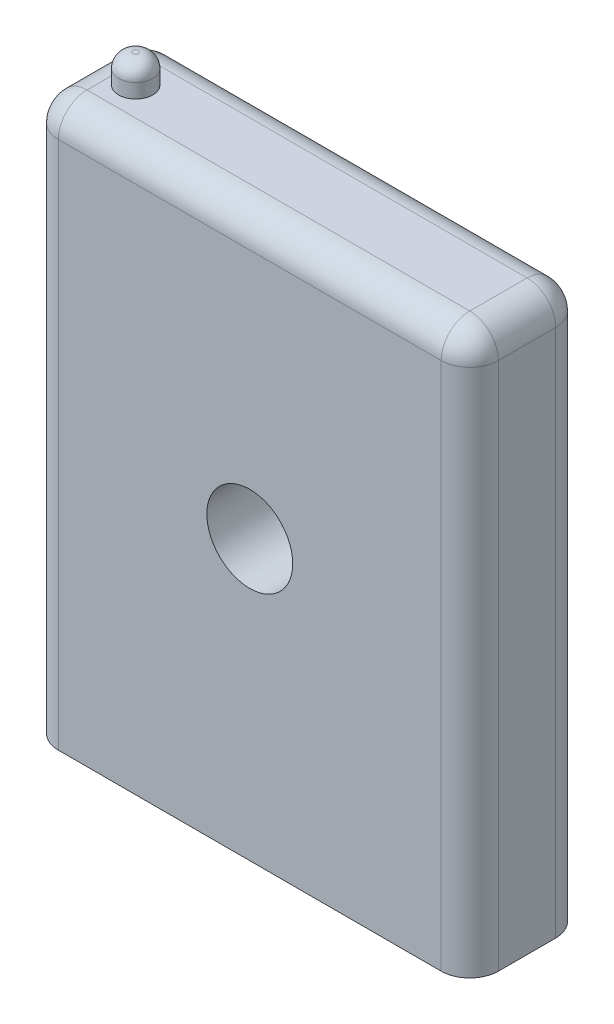
SolidWorks part; units mm, degrees
ref_plane "Front Plane" through (0, 0, 0) normal (0, 0, 1) x (1, 0, 0)
ref_plane "Top Plane" through (0, 0, 0) normal (0, 1, 0) x (1, 0, 0)
ref_plane "Right Plane" through (0, 0, 0) normal (1, 0, 0) x (0, 0, -1)
sketch "Sketch1" plane through (0, 0, 0) normal (0, 0, 1) x (1, 0, 0)
  line L1 (-2.2248, 20.0232) -> (74.6543, 20.0232)
  line L2 (-2.2248, 20.0232) -> (-2.2248, -77.3735)
  line L3 (-2.2248, -77.3735) -> (74.6543, -77.3735)
  line L4 (74.6543, 20.0232) -> (74.6543, -77.3735)
extrude "Boss-Extrude1" add sketch "Sketch1" along normal blind 20
sketch "Sketch2" plane through (0, 0, 20) normal (0, 0, 1) x (1, 0, 0)
  line L0 (-2.2248, -28.6752) -> (74.6543, -28.6752) construction
  line L1 (-2.2248, 20.0232) -> (-2.2248, -77.3735) construction
  line L2 (74.6543, -77.3735) -> (74.6543, 20.0232) construction
  circle A0 centre (36.2147, -28.6752) radius 7.5
  dimension "D1" = 15
extrude "Cut-Extrude1" cut sketch "Sketch2" against normal blind 20
fillet "Fillet2" radius 5 1 edges at (74.6543, 20.0232, 10)
fillet "Fillet3" radius 5 3 edges at (74.6543, -31.1752, 20) (73.1898, 18.5587, 20) (33.7147, 20.0232, 20)
fillet "Fillet4" radius 5 3 edges at (74.6543, -31.1752, 0) (73.1898, 18.5587, 0) (33.7147, 20.0232, 0)
fillet "Fillet5" radius 5 5 edges at (-2.2248, -31.1752, 20) (-2.2248, 18.5587, 18.5355) (-2.2248, -31.1752, 0) (-2.2248, 18.5587, 1.4645) (-2.2248, 20.0232, 10)
sketch "Sketch3" plane through (0, 20.0232, 0) normal (0, 1, 0) x (1, 0, 0)
  line L0 (69.6543, -10) -> (2.7752, -10) construction
  line L1 (69.6543, -15) -> (69.6543, -5) construction
  line L2 (2.7752, -5) -> (2.7752, -15) construction
  circle A0 centre (6.2864, -10) radius 2.9965
extrude "Boss-Extrude2" add sketch "Sketch3" along normal blind 5
fillet "Fillet7" radius 2.5 1 edges at (6.2864, 25.0232, 12.9965)
